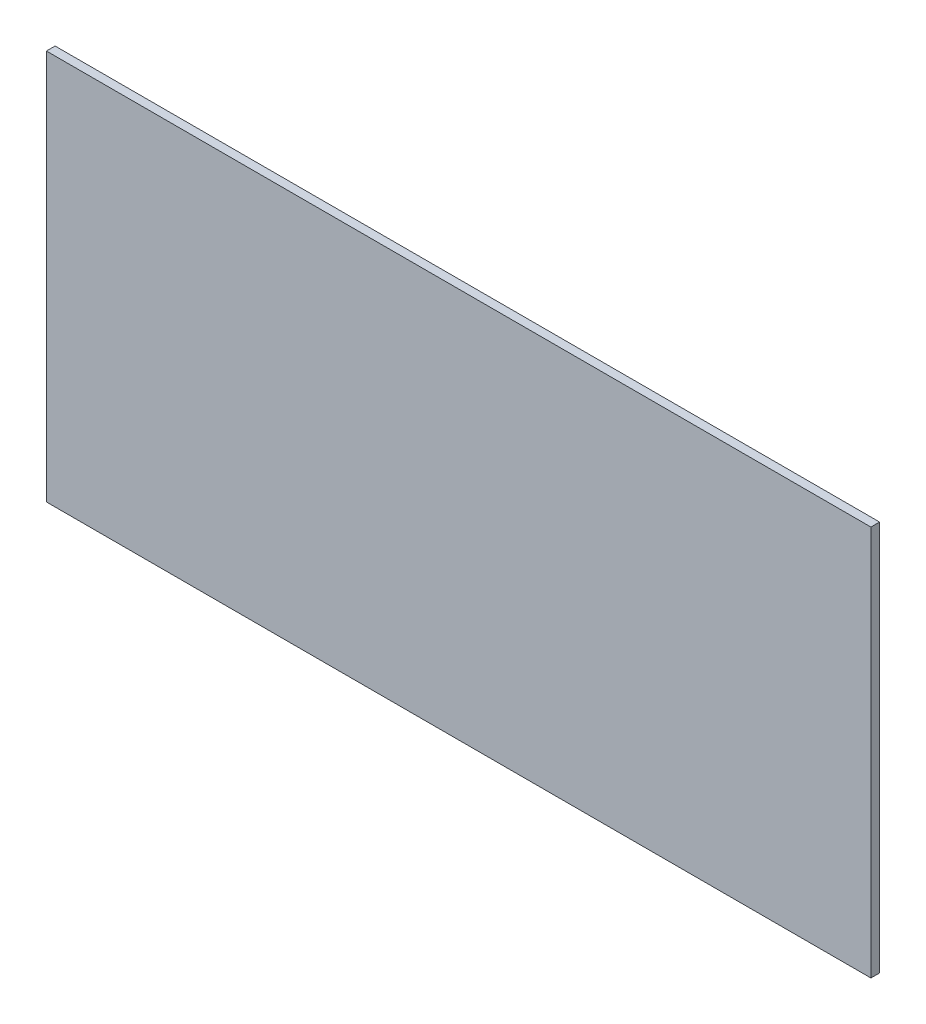
SolidWorks part; units mm, degrees
ref_plane "Front Plane" through (0, 0, 0) normal (0, 0, 1) x (1, 0, 0)
ref_plane "Top Plane" through (0, 0, 0) normal (0, 1, 0) x (1, 0, 0)
ref_plane "Right Plane" through (0, 0, 0) normal (1, 0, 0) x (0, 0, -1)
sketch "Sketch1" plane through (0, 0, 0) normal (0, 0, 1) x (1, 0, 0)
  line L1 (0, 0) -> (190, 0)
  line L2 (0, 0) -> (0, 90)
  line L3 (0, 90) -> (190, 90)
  line L4 (190, 0) -> (190, 90)
  dimension "D1" = 190
  dimension "D2" = 90
extrude "Profile" add sketch "Sketch1" along normal blind 2
equation "\"Profile_Depth\" = 2mm"
equation "\"D1@Profile\" = \"Profile_Depth\""
equation "\"EnvelopeWidth\" = 190mm"
equation "\"EnvelopeHeight\" = 90mm"
